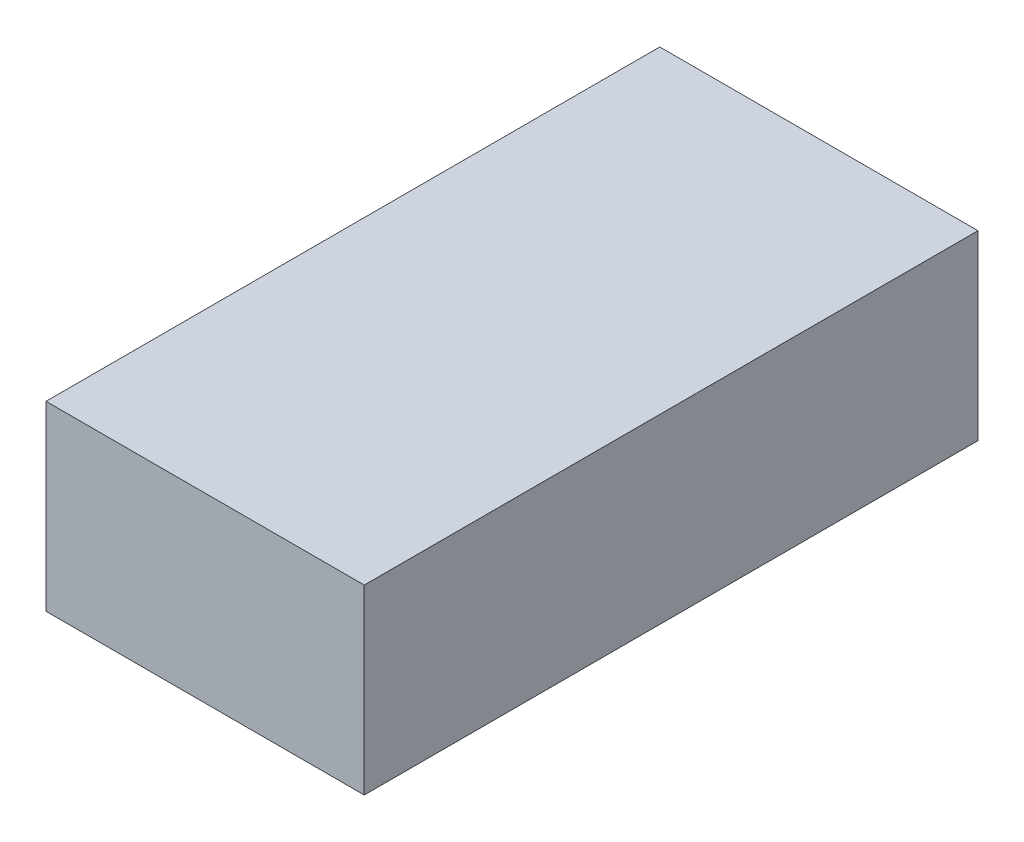
SolidWorks part; units mm, degrees
ref_plane "Front Plane" through (0, 0, 0) normal (0, 0, 1) x (1, 0, 0)
ref_plane "Top Plane" through (0, 0, 0) normal (0, 1, 0) x (1, 0, 0)
ref_plane "Right Plane" through (0, 0, 0) normal (1, 0, 0) x (0, 0, -1)
sketch "Sketch1" plane through (0, 0, 0) normal (0, 1, 0) x (1, 0, 0)
  line L1 (-22.225, 42.8625) -> (22.225, 42.8625)
  line L2 (-22.225, 42.8625) -> (-22.225, -42.8625)
  line L3 (-22.225, -42.8625) -> (22.225, -42.8625)
  line L4 (22.225, 42.8625) -> (22.225, -42.8625)
  point P4 (0, 42.8625)
  point P6 (-22.225, 0)
  dimension "D1" = 44.45
  dimension "D2" = 85.725
extrude "Boss-Extrude1" add sketch "Sketch1" along normal blind 25.4
